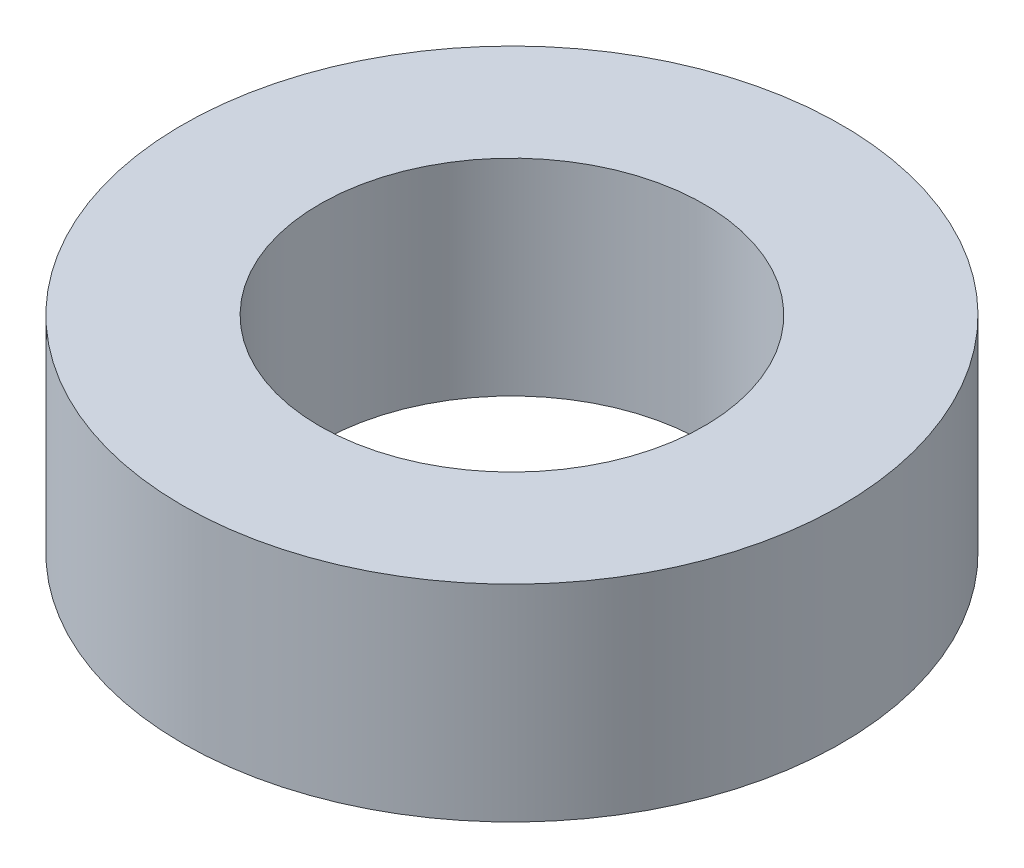
SolidWorks part; units mm, degrees
ref_plane "Front Plane" through (0, 0, 0) normal (0, 0, 1) x (1, 0, 0)
ref_plane "Top Plane" through (0, 0, 0) normal (0, 1, 0) x (1, 0, 0)
ref_plane "Right Plane" through (0, 0, 0) normal (1, 0, 0) x (0, 0, -1)
sketch "Sketch1" plane through (0, 0, 0) normal (0, 1, 0) x (1, 0, 0)
  circle A0 centre (0, 0) radius 3.5
  circle A1 centre (0, 0) radius 6
  dimension "D1" = 7
  dimension "D2" = 2.5
extrude "Boss-Extrude1" add sketch "Sketch1" along normal blind 3.75
